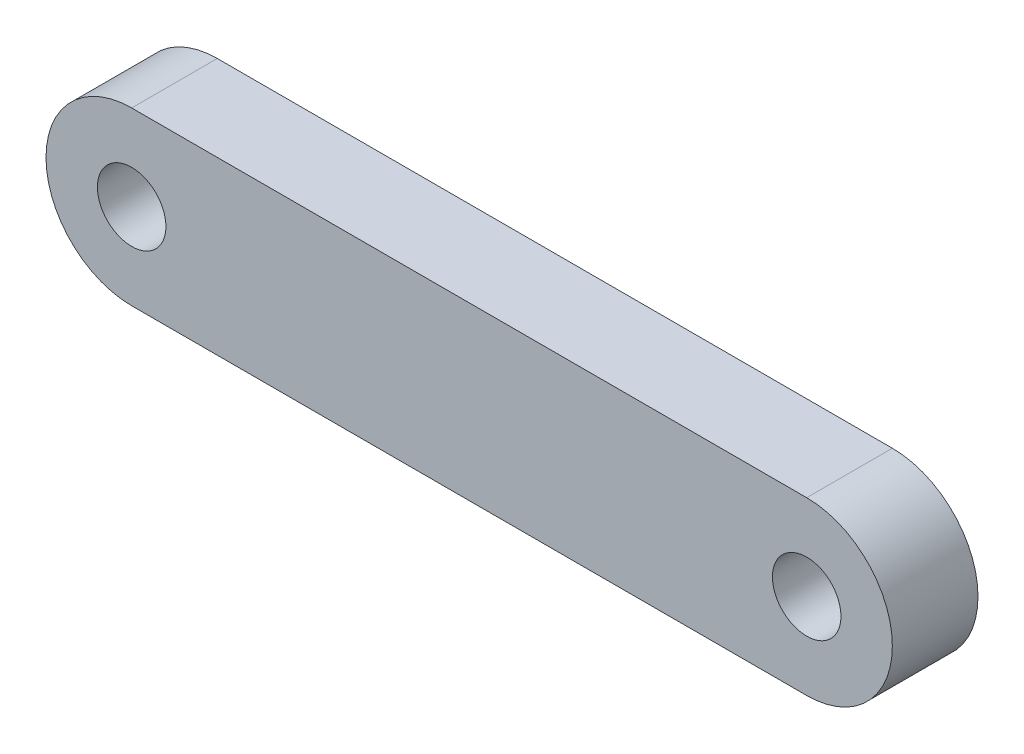
SolidWorks part; units mm, degrees
ref_plane "前基準面" through (0, 0, 0) normal (0, 0, 1) x (1, 0, 0)
ref_plane "上基準面" through (0, 0, 0) normal (0, 1, 0) x (1, 0, 0)
ref_plane "右基準面" through (0, 0, 0) normal (1, 0, 0) x (0, 0, -1)
sketch "草圖2" plane through (0, 0, 0) normal (0, 0, 1) x (1, 0, 0)
  line L0 (-19.7, 0) -> (19.7, 0) construction
  line L1 (-19.7, 5) -> (19.7, 5)
  line L2 (-19.7, -5) -> (19.7, -5)
  arc A0 (-19.7, 5) -> (-19.7, -5) centre (-19.7, 0) ccw
  arc A1 (19.7, -5) -> (19.7, 5) centre (19.7, 0) ccw
  circle A2 centre (19.7, 0) radius 2
  circle A3 centre (-19.7, 0) radius 2
  point P2 (0, 0)
  dimension "D2" = 4
  dimension "D3" = 5
  dimension "D1" = 39.4
extrude "填料-伸長1" add sketch "草圖2" along normal mid plane 5
